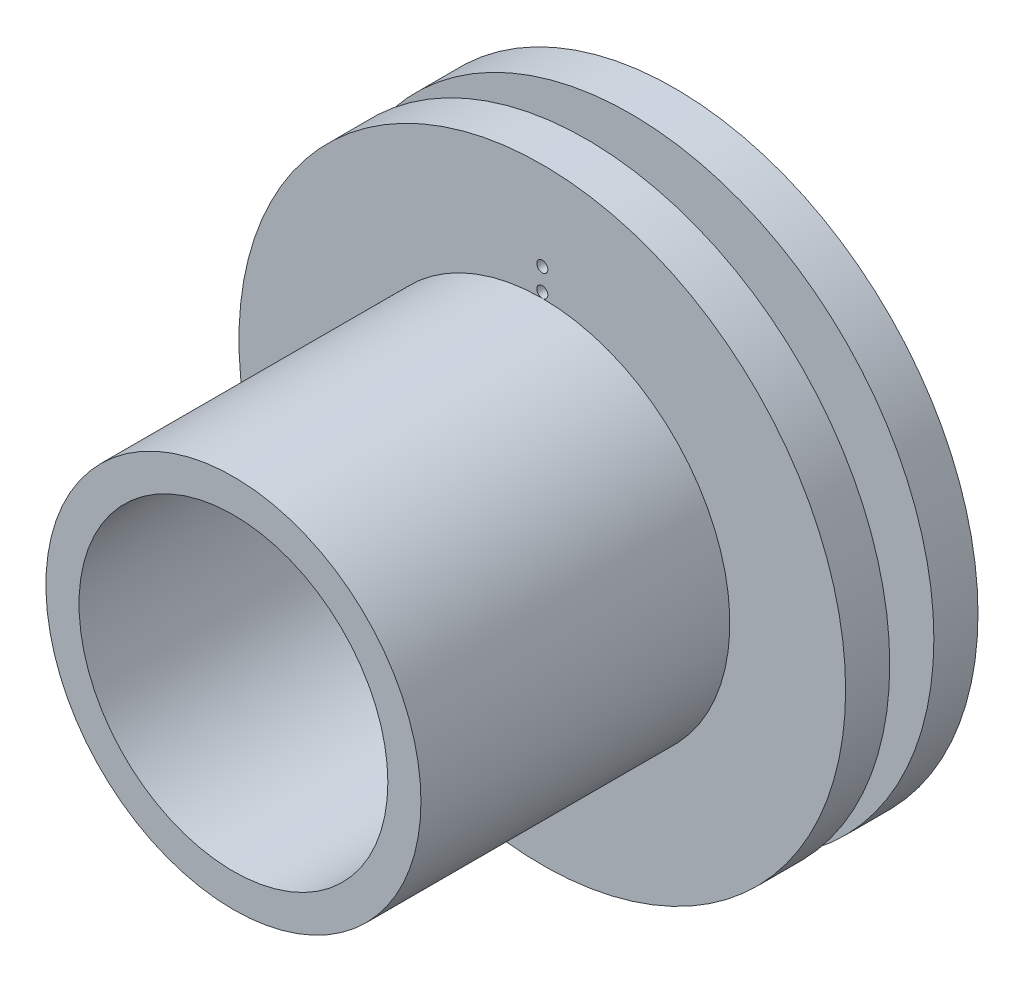
SolidWorks part; units mm, degrees
material "ABS"
ref_plane "Front Plane" through (0, 0, 0) normal (0, 0, 1) x (1, 0, 0)
ref_plane "Top Plane" through (0, 0, 0) normal (0, 1, 0) x (1, 0, 0)
ref_plane "Right Plane" through (0, 0, 0) normal (1, 0, 0) x (0, 0, -1)
sketch "Sketch1" plane through (0, 0, 0) normal (0, 0, 1) x (1, 0, 0)
  circle A0 centre (0, 0) radius 13.75
  dimension "D1" = 27.5
extrude "Boss-Extrude1" add sketch "Sketch1" along normal blind 2
sketch "Sketch2" plane through (0, 0, 0) normal (0, 0, 1) x (1, 0, 0)
  circle A0 centre (0, 0) radius 8.5
  dimension "D1" = 17
extrude "Boss-Extrude2" add sketch "Sketch2" along normal blind 6
sketch "Sketch3" plane through (0, 0, 0) normal (0, 0, 1) x (1, 0, 0)
  circle A0 centre (0, 0) radius 13.75
  dimension "D1" = 27.5
extrude "Boss-Extrude3" add sketch "Sketch3" along normal blind 2 from offset 4
sketch "Sketch5" plane through (0, 0, 0) normal (0, 0, 1) x (1, 0, 0)
  circle A0 centre (0, 0) radius 7
extrude "Cut-Extrude2" cut sketch "Sketch5" along normal through all
sketch "Sketch6" plane through (0, 0, 0) normal (0, 0, 1) x (1, 0, 0)
  circle A0 centre (0, 0) radius 7
  circle A1 centre (0, 0) radius 8.5
  dimension "D1" = 17
extrude "Boss-Extrude4" add sketch "Sketch6" along normal blind 14 from surface at 6 starting at face at (13.75, 0, 6)
sketch "Sketch9" plane through (0, 0, 0) normal (0, 0, 1) x (1, 0, 0)
  circle A0 centre (0, 9.75) radius 0.25
  circle A1 centre (0, -9.75) radius 0.25
  circle A2 centre (0, 8.75) radius 0.25
  circle A3 centre (0, -8.75) radius 0.25
extrude "Cut-Extrude3" cut sketch "Sketch9" along normal through all from surface at 4 starting at face at (13.75, 0, 4)
